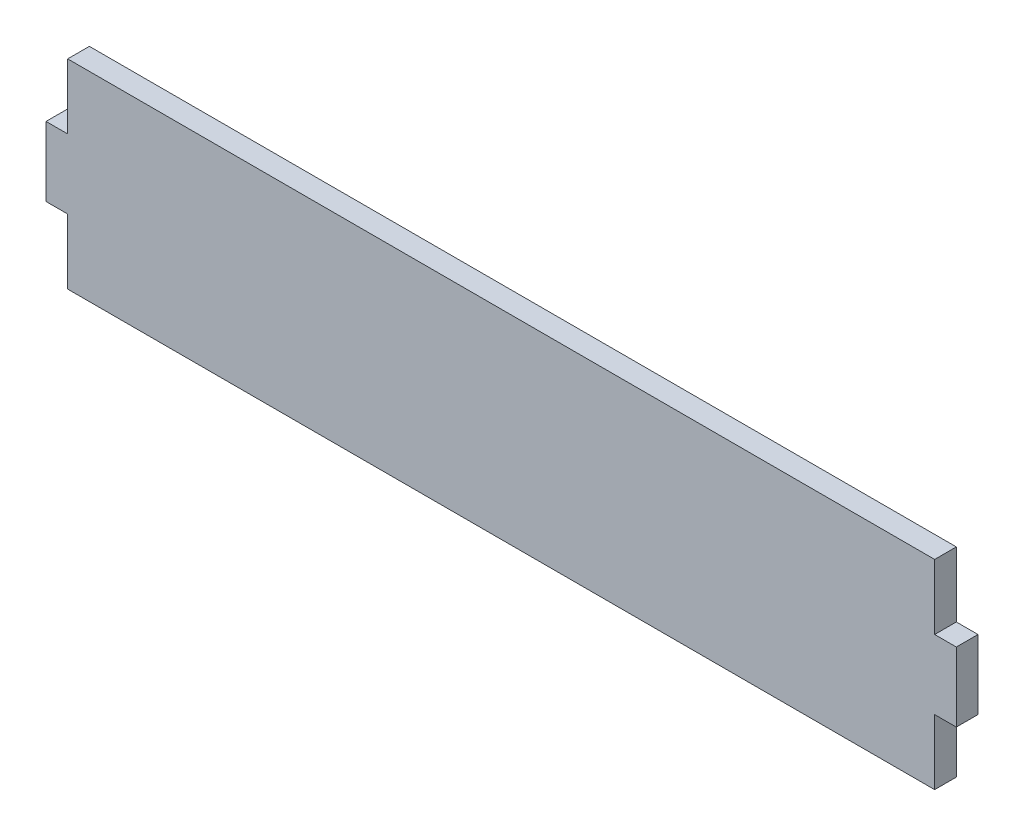
SolidWorks part; units mm, degrees
material "Beech"
ref_plane "Front" through (0, 0, 0) normal (0, 0, 1) x (1, 0, 0)
ref_plane "Top" through (0, 0, 0) normal (0, 1, 0) x (1, 0, 0)
ref_plane "Right" through (0, 0, 0) normal (1, 0, 0) x (0, 0, -1)
sketch "Sketch1" plane through (0, 0, 0) normal (0, 0, 1) x (1, 0, 0)
  line L0 (0, -5.6139) -> (0, 7.3412) construction
  line L1 (-52.5, -11.5) -> (52.5, -11.5) construction
  line L2 (-52.5, -11.5) -> (-52.5, 11.5) construction
  line L3 (-52.5, 11.5) -> (52.5, 11.5) construction
  line L4 (52.5, -11.5) -> (52.5, 11.5) construction
  line L5 (-52.5, -11.5) -> (52.5, 11.5) construction
  line L6 (-52.5, 11.5) -> (52.5, -11.5) construction
  line L7 (50, -4) -> (52.5, -4)
  line L8 (50, -4) -> (50, 4) construction
  line L9 (50, 4) -> (52.5, 4)
  line L10 (52.5, -4) -> (52.5, 4)
  line L11 (50, -4) -> (52.5, 4) construction
  line L12 (50, 4) -> (52.5, -4) construction
  line L13 (-50, 4) -> (-52.5, 4)
  line L14 (-52.5, -4) -> (-52.5, 4)
  line L15 (-50, -4) -> (-52.5, -4)
  line L16 (-50, -4) -> (-50, 4) construction
  line L17 (-50, 4) -> (-50, 11.5)
  line L18 (-50, 11.5) -> (50, 11.5)
  line L19 (50, 11.5) -> (50, 4)
  line L20 (50, -4) -> (50, -11.5)
  line L21 (50, -11.5) -> (-50, -11.5)
  line L22 (-50, -11.5) -> (-50, -4)
  point P0 (0, 0)
  point P6 (51.25, 0)
  dimension "D1" = 105
  dimension "D3" = 2.5
  dimension "D4" = 8
  dimension "D5" = 23
extrude "Boss-Extrude1" add sketch "Sketch1" along normal blind 2.5
